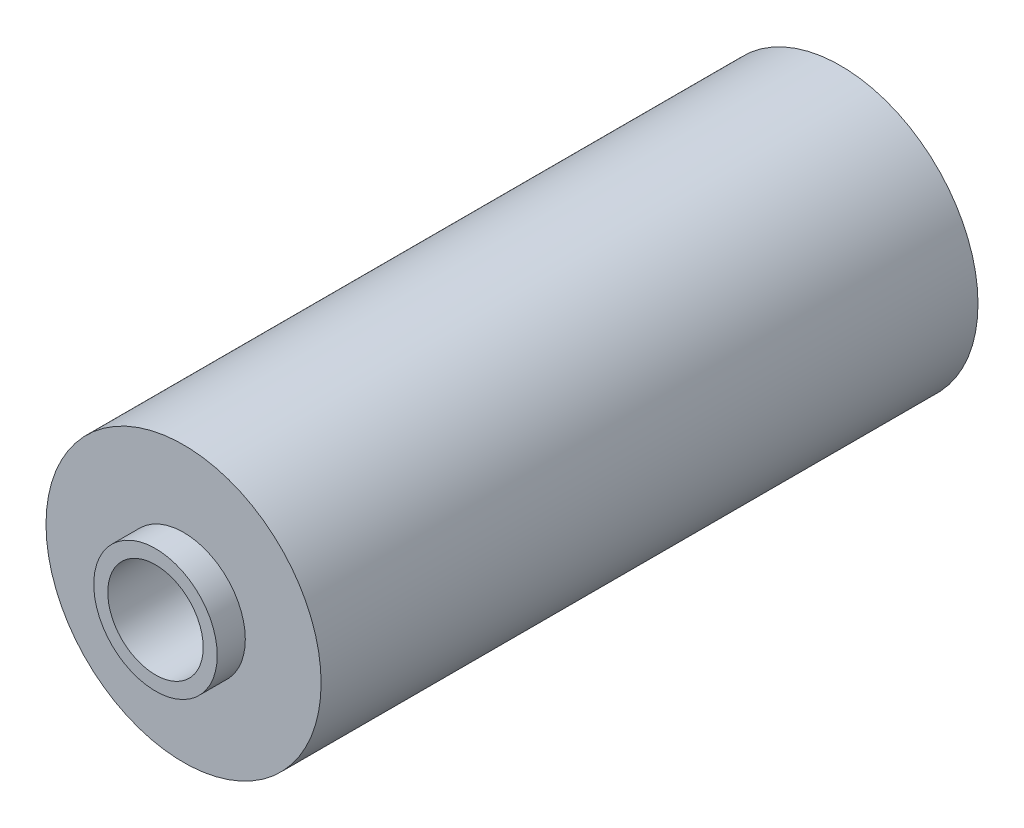
SolidWorks part; units mm, degrees
ref_plane "Front Plane" through (0, 0, 0) normal (0, 0, 1) x (1, 0, 0)
ref_plane "Top Plane" through (0, 0, 0) normal (0, 1, 0) x (1, 0, 0)
ref_plane "Right Plane" through (0, 0, 0) normal (1, 0, 0) x (0, 0, -1)
sketch "Sketch1" plane through (0, 0, 0) normal (0, 0, 1) x (1, 0, 0)
  circle A0 centre (0, 0) radius 1.7
  circle A2 centre (0, 0) radius 4.9
  dimension "D1" = 3.4
  dimension "D2" = 9.8
extrude "Boss-Extrude1" add sketch "Sketch1" along normal blind 23.4
sketch "Sketch2" plane through (0, 0, 23.4) normal (0, 0, 1) x (1, 0, 0)
  circle A0 centre (0, 0) radius 1.7
  circle A2 centre (0, 0) radius 2.2
  dimension "D1" = 3.4
  dimension "D2" = 0.5
extrude "Boss-Extrude2" add sketch "Sketch2" along normal blind 1
sketch "Sketch3" plane through (0, 0, 0) normal (0, 0, 1) x (1, 0, 0)
  circle A0 centre (0, 0) radius 2.2
  circle A1 centre (0, 0) radius 1.7
  dimension "D1" = 4.4
  dimension "D2" = 3.4
